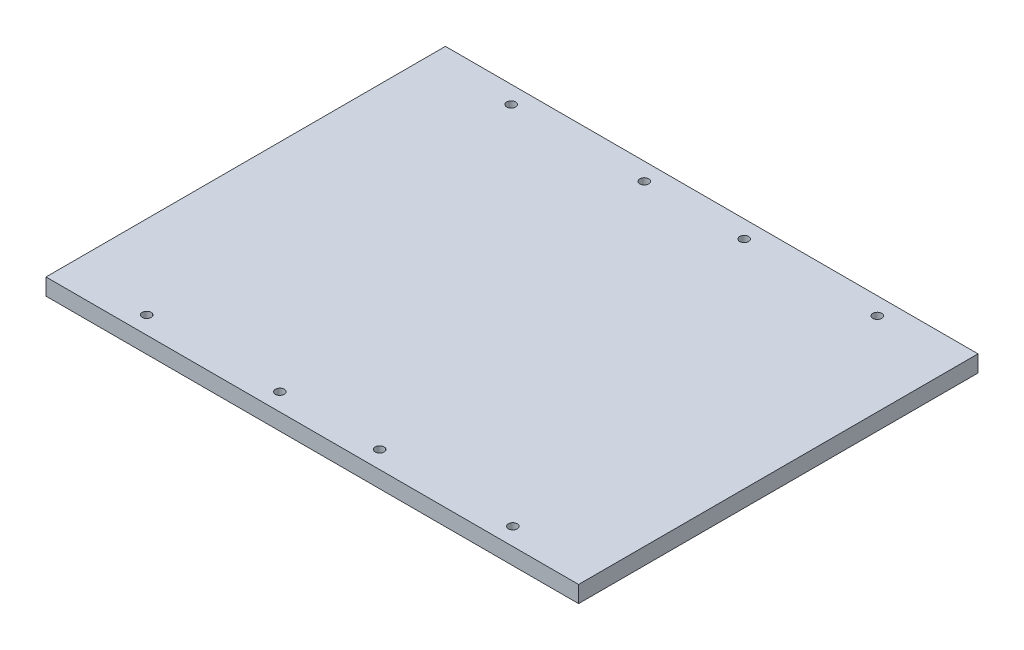
SolidWorks part; units mm, degrees
material "Acrylic (Medium-high impact)"
ref_plane "Front Plane" through (0, 0, 0) normal (0, 0, 1) x (1, 0, 0)
ref_plane "Top Plane" through (0, 0, 0) normal (0, 1, 0) x (1, 0, 0)
ref_plane "Right Plane" through (0, 0, 0) normal (1, 0, 0) x (0, 0, -1)
sketch "Sketch1" plane through (0, 0, 0) normal (0, 1, 0) x (1, 0, 0)
  line L0 (0, 76.2) -> (0, -76.2) construction
  line L1 (-51.435, 63.5) -> (-42.545, 63.5) construction
  line L2 (101.6, -76.2) -> (-101.6, -76.2)
  line L3 (101.6, -76.2) -> (101.6, 76.2)
  line L4 (101.6, 76.2) -> (-101.6, 76.2)
  line L5 (-101.6, -76.2) -> (-101.6, 76.2)
  line L6 (101.6, -76.2) -> (-101.6, 76.2) construction
  line L7 (101.6, 76.2) -> (-101.6, -76.2) construction
  line L8 (-89.535, 63.5) -> (-51.435, 63.5) construction
  line L9 (-89.535, 63.5) -> (-89.535, -63.5) construction
  line L10 (-89.535, -63.5) -> (-51.435, -63.5) construction
  line L11 (-51.435, 63.5) -> (-51.435, -63.5) construction
  line L12 (-42.545, 63.5) -> (-4.445, 63.5) construction
  line L13 (-42.545, 63.5) -> (-42.545, -63.5) construction
  line L14 (-42.545, -63.5) -> (-4.445, -63.5) construction
  line L15 (-4.445, 63.5) -> (-4.445, -63.5) construction
  line L16 (4.445, 63.5) -> (42.545, 63.5) construction
  line L17 (4.445, 63.5) -> (4.445, -63.5) construction
  line L18 (4.445, -63.5) -> (42.545, -63.5) construction
  line L19 (42.545, 63.5) -> (42.545, -63.5) construction
  line L20 (51.435, 63.5) -> (89.535, 63.5) construction
  line L21 (51.435, 63.5) -> (51.435, -63.5) construction
  line L22 (51.435, -63.5) -> (89.535, -63.5) construction
  line L23 (89.535, 63.5) -> (89.535, -63.5) construction
  line L24 (-4.445, 63.5) -> (4.445, 63.5) construction
  line L25 (42.545, 63.5) -> (51.435, 63.5) construction
  line L26 (-4.445, 0) -> (4.445, 0) construction
  line L27 (-92.075, 44.45) -> (-99.06, 44.45) construction
  line L28 (-99.06, 44.45) -> (-99.06, 74.295) construction
  line L29 (-99.06, 74.295) -> (99.06, 74.295) construction
  line L30 (99.06, 74.295) -> (99.06, 44.45) construction
  line L31 (99.06, 44.45) -> (92.075, 44.45) construction
  line L32 (92.075, 44.45) -> (92.075, 64.77) construction
  line L33 (92.075, 64.77) -> (48.895, 64.77) construction
  line L34 (48.895, 64.77) -> (48.895, 44.45) construction
  line L35 (48.895, 44.45) -> (45.085, 44.45) construction
  line L36 (45.085, 44.45) -> (45.085, 64.77) construction
  line L37 (45.085, 64.77) -> (1.905, 64.77) construction
  line L38 (1.905, 64.77) -> (1.905, 44.45) construction
  line L39 (1.905, 44.45) -> (-1.905, 44.45) construction
  line L40 (-1.905, 44.45) -> (-1.905, 64.77) construction
  line L41 (-1.905, 64.77) -> (-45.085, 64.77) construction
  line L42 (-45.085, 64.77) -> (-45.085, 44.45) construction
  line L43 (-45.085, 44.45) -> (-48.895, 44.45) construction
  line L44 (-48.895, 44.45) -> (-48.895, 64.77) construction
  line L45 (-48.895, 64.77) -> (-92.075, 64.77) construction
  line L46 (-92.075, 64.77) -> (-92.075, 44.45) construction
  line L47 (-99.06, 74.295) -> (-101.6, 74.295) construction
  line L48 (-99.06, 69.5325) -> (99.06, 69.5325) construction
  circle A0 centre (-69.85, 69.5325) radius 1.7
  circle A1 centre (-19.05, 69.5325) radius 1.7
  circle A2 centre (19.05, 69.5325) radius 1.7
  circle A3 centre (69.85, 69.5325) radius 1.7
  circle A4 centre (-69.85, -69.5325) radius 1.7
  circle A5 centre (69.85, -69.5325) radius 1.7
  circle A6 centre (19.05, -69.5325) radius 1.7
  circle A7 centre (-19.05, -69.5325) radius 1.7
  point P23 (-4.445, 0)
  point P24 (4.445, 0)
  point P27 (0, 0)
  dimension "D19" = 3.4
  dimension "D1" = 152.4
  dimension "D2" = 127
  dimension "D3" = 38.1
  dimension "D4" = 8.89
  dimension "D5" = 203.2
  dimension "D7" = 2.54
  dimension "D8" = 2.54
  dimension "D9" = 2.54
  dimension "D10" = 2.54
  dimension "D11" = 2.54
  dimension "D15" = 2.54
  dimension "D17" = 9.525
  dimension "D18" = 2.54
  dimension "D20" = 4.7625
  dimension "D21" = 19.05
  dimension "D22" = 50.8
  dimension "D23" = 19.05
  dimension "D24" = 50.8
extrude "Boss-Extrude1" add sketch "Sketch1" along normal blind 6.35
equation "\"D20@Sketch1\"=\"D17@Sketch1\"/2"
equation "\"D23@Sketch1\"=\"D21@Sketch1\""
equation "\"D24@Sketch1\"=\"D22@Sketch1\""
